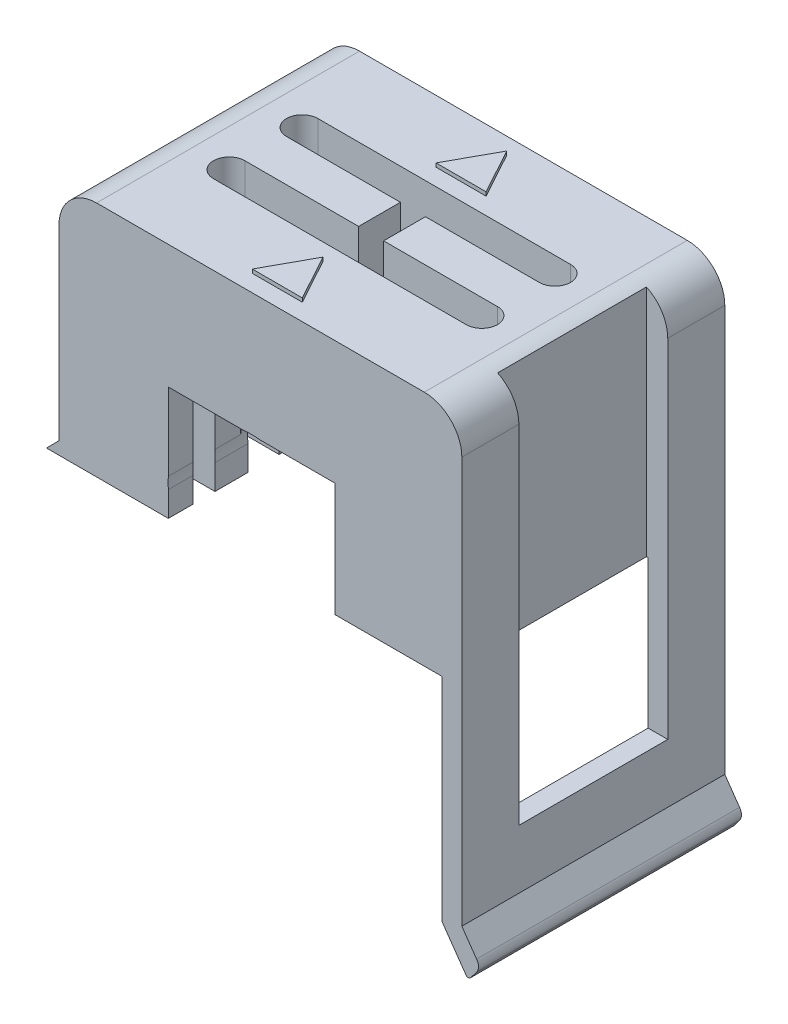
SolidWorks part; units mm, degrees
material "PET"
ref_plane "Alzado" through (0, 0, 0) normal (0, 0, 1) x (1, 0, 0)
ref_plane "Planta" through (0, 0, 0) normal (0, 1, 0) x (1, 0, 0)
ref_plane "Vista lateral" through (0, 0, 0) normal (1, 0, 0) x (0, 0, -1)
sketch "Croquis2" plane through (0, 0, 0) normal (0, 0, 1) x (1, 0, 0)
  line L0 (16.1, -9.1) -> (16.1, -25.6)
  line L1 (-13.1, 9.87) -> (13.1, 9.87)
  line L2 (-16.1, 6.87) -> (-16.1, -8.0848)
  line L3 (-16.1, -9.1) -> (-7.36, -9.1)
  line L4 (16.1, 6.87) -> (16.1, -9.1)
  line L5 (-16.1, 9.87) -> (-14.9972, 9.1939) construction
  line L6 (5.96, -9.1) -> (14.53, -9.1)
  line L7 (14.53, -9.1) -> (14.53, -26.095)
  line L8 (16.1, -25.6) -> (17.282, -27.2881)
  line L9 (14.53, -26.095) -> (16.4629, -28.8555)
  line L10 (17.285, -28.1847) -> (16.8104, -28.8058)
  line L11 (14.53, -26.095) -> (15.9959, -28.1886) construction
  line L12 (14.9783, 9.2092) -> (16.1, 9.87) construction
  line L13 (-16.1, -8.0848) -> (-17.1, -9.1)
  line L14 (-7.36, -9.1) -> (-7.36, -7.1)
  line L15 (5.96, -9.1) -> (5.96, -7.1)
  line L16 (-17.1, -9.1) -> (-16.1, -9.1)
  arc A0 (16.1, 6.87) -> (13.1, 9.87) centre (13.1, 6.87) ccw
  arc A1 (-16.1, 6.87) -> (-13.1, 9.87) centre (-13.1, 6.87) cw
  arc A2 (17.282, -27.2881) -> (17.285, -28.1847) centre (16.7008, -27.7383) cw
  arc A3 (16.8216, -28.7911) -> (16.4629, -28.8555) centre (16.6094, -28.6405) cw
  arc A4 (-7.36, -7.1) -> (5.96, -7.1) centre (-0.7, -6.6391) cw
  point P0 (0, 0)
  dimension "D3" = 3
  dimension "D1" = 32.2
  dimension "D2" = 18.97
  dimension "D4" = 1.57
  dimension "D5" = 16.5
  dimension "D6" = 1
  dimension "D7" = 145
  dimension "D9" = 2
  dimension "D10" = 2
extrude "Saliente-Extruir1" add sketch "Croquis2" along normal blind 21.02 contours L14 A4 L15 L6 L7 L9 A3 L10 A2 L8 L0 L4 A0 L1 A1 L2 L13 L16 L3
sketch "Croquis3" plane through (0, 9.87, 0) normal (0, 1, 0) x (1, 0, 0)
  line L2 (-10.1, -13.42) -> (10.1, -13.42) construction
  line L3 (-10.1, -12.17) -> (-1, -12.17)
  line L4 (-10.1, -14.67) -> (10.1, -14.67)
  line L6 (-10.1, -7.58) -> (10.1, -7.58) construction
  line L7 (-10.1, -6.33) -> (10.1, -6.33)
  line L8 (-10.1, -8.83) -> (-1, -8.83)
  line L10 (-1, -8.83) -> (-1, -12.17)
  line L11 (1, -8.83) -> (1, -12.17)
  line L12 (1, -8.83) -> (10.1, -8.83)
  line L13 (1, -12.17) -> (10.1, -12.17)
  arc A0 (-10.1, -12.17) -> (-10.1, -14.67) centre (-10.1, -13.42) ccw
  arc A1 (10.1, -14.67) -> (10.1, -12.17) centre (10.1, -13.42) ccw
  arc A2 (-10.1, -6.33) -> (-10.1, -8.83) centre (-10.1, -7.58) ccw
  arc A3 (10.1, -8.83) -> (10.1, -6.33) centre (10.1, -7.58) ccw
  point P7 (0, -14.81)
  point P16 (0, -10.2)
  point P24 (0, -12.348)
  dimension "D3" = 3.34
  dimension "D2" = 20.2
extrude "Cortar-Extruir1" cut sketch "Croquis3" against normal through all
sketch "Croquis4" plane through (0, 9.87, 0) normal (0, 1, 0) x (-1, 0, 0)
  line L4 (0, 16.02) -> (2, 19.67)
  line L5 (0, 16.02) -> (-2, 19.67)
  line L6 (2, 19.67) -> (-2, 19.67)
  line L9 (2, 4.98) -> (-2, 4.98)
  line L10 (0, 1.33) -> (2, 4.98)
  line L11 (0, 1.33) -> (-2, 4.98)
extrude "Saliente-Extruir2" add sketch "Croquis4" along normal blind 0.3
sketch "Croquis5" plane through (16.1, 0, 0) normal (1, 0, 0) x (0, 0, -1)
  line L0 (-10.51, -25.6) -> (-10.51, -20.9)
  line L1 (-21.02, -25.6) -> (0, -25.6) construction
  line L2 (-16.46, -20.9) -> (-4.56, -20.9)
  line L3 (-16.46, -20.9) -> (-16.46, 9.8154)
  line L4 (-16.46, 9.8154) -> (-4.56, 10.17)
  line L5 (-4.98, 10.17) -> (-1.33, 10.17) construction
  line L6 (-4.56, 10.17) -> (-4.56, -20.9)
  line M2 (0, 6.87) -> (-21.02, 6.87)
  dimension "D1" = 4.7
  dimension "D2" = 5.95
extrude "Cortar-Extruir2" cut sketch "Croquis5" against normal blind 1.7 contours L6 L3 L2 M2 | L6 L4 L3 M2
sketch "Croquis6" plane through (0, 0, 0) normal (0, 0, -1) x (-1, 0, 0)
  line L0 (-5.96, -9.1) -> (-5.96, 0)
  line L1 (-5.96, 0) -> (7.36, 0)
  line L2 (7.36, 0) -> (7.36, -9.1)
  line L3 (7.36, -9.1) -> (7.36, -7.1) construction
  line L4 (-5.96, -9.1) -> (7.36, -9.1)
extrude "Cortar-Extruir3" cut sketch "Croquis6" against normal blind 5.78
sketch "Croquis7" plane through (0, 0, 21.02) normal (0, 0, 1) x (1, 0, 0)
  line L0 (-7.36, -9.1) -> (-7.36, 0)
  line L1 (-7.36, 0) -> (5.96, 0)
  line L2 (5.96, -9.1) -> (5.96, 0)
  line L3 (-7.36, -9.1) -> (5.96, -9.1)
extrude "Cortar-Extruir4" cut sketch "Croquis7" against normal blind 5.78
sketch "Croquis8" plane through (0, -9.1, 0) normal (0, -1, 0) x (1, 0, 0)
  line L0 (-1, 10.5) -> (-4.3919, 10.5)
  line L2 (14.53, 21.02) -> (14.53, 16.46) construction
  line L3 (-9.5523, 19.04) -> (14.53, 19.04)
  line L4 (-1, 8.83) -> (-1, 12.17) construction
  line L5 (-9.5523, 17.2942) -> (14.53, 17.2942)
  line L6 (14.53, 19.04) -> (14.53, 17.2942)
  line L7 (-15.51, 1.96) -> (-15.51, 3.7058)
  line L9 (-9.5523, 3.7058) -> (-15.51, 3.7058)
  line L10 (-9.5523, 19.04) -> (-15.51, 19.04)
  line L11 (-9.5523, 1.96) -> (-15.51, 1.96)
  line L12 (-9.5523, 17.2942) -> (-15.51, 17.2942)
  line L13 (-15.51, 19.04) -> (-15.51, 17.2942)
  line L14 (14.53, 1.96) -> (14.53, 3.7058)
  line L15 (-9.5523, 3.7058) -> (14.53, 3.7058)
  line L16 (-9.5523, 1.96) -> (14.53, 1.96)
  line M7 (-7.36, 14.67) -> (-7.36, 21.02)
  line M11 (-7.36, 0) -> (-7.36, 6.33)
extrude "Cortar-Extruir5" cut sketch "Croquis8" against normal blind 15.76 contours L10 L13 L12 L5 L3 M7 | L6 L3 L5 M7 | L16 L14 L15 M11 | L11 L16 L15 L9 L7 M11
